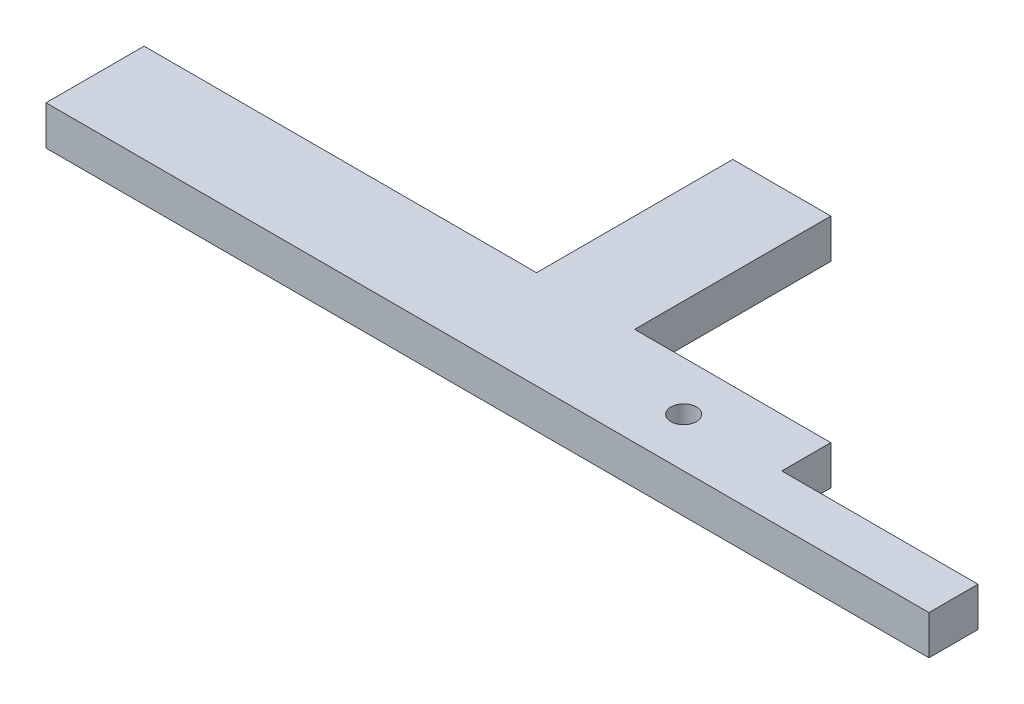
SolidWorks part; units mm, degrees
ref_plane "Front Plane" through (0, 0, 0) normal (0, 0, 1) x (1, 0, 0)
ref_plane "Top Plane" through (0, 0, 0) normal (0, 1, 0) x (1, 0, 0)
ref_plane "Right Plane" through (0, 0, 0) normal (1, 0, 0) x (0, 0, -1)
sketch "Sketch1" plane through (0, 0, 0) normal (0, 1, 0) x (1, 0, 0)
  line L0 (-25.4, 12.7) -> (25.4, 12.7)
  line L1 (-152.4, 12.7) -> (-50.8, 12.7)
  line L2 (-152.4, 12.7) -> (-152.4, -12.7)
  line L3 (-152.4, -12.7) -> (25.4, -12.7)
  line L4 (25.4, 12.7) -> (25.4, 0)
  line L6 (25.4, -12.7) -> (76.2, -12.7)
  line L7 (-48.8383, -12.7) -> (-34.673, -12.7)
  line L8 (-50.8, 12.7) -> (-50.8, 63.5)
  line L9 (-50.8, 63.5) -> (-25.4, 63.5)
  line L10 (-25.4, 12.7) -> (-25.4, 63.5)
  line L12 (25.4, 0) -> (76.2, 0)
  line L13 (76.2, -12.7) -> (76.2, 0)
  circle A0 centre (0, 0) radius 3.302
  point P4 (-38.1, 63.5)
  point P19 (0, 0)
  point P20 (79.3958, -19.05)
  point P21 (0, 0)
  point P22 (0, 0)
  point P23 (0, 0)
  dimension "D7" = 6.604
  dimension "D1" = 25.4
  dimension "D2" = 25.4
  dimension "D3" = 152.4
  dimension "D4" = 38.1
  dimension "D5" = 25.4
  dimension "D6" = 50.8
  dimension "D8" = 50.8
  dimension "D9" = 12.7
extrude "Boss-Extrude1" add sketch "Sketch1" along normal blind 10.16 contours L0 L10 L9 L8 L1 L2 L3 L4 A0
